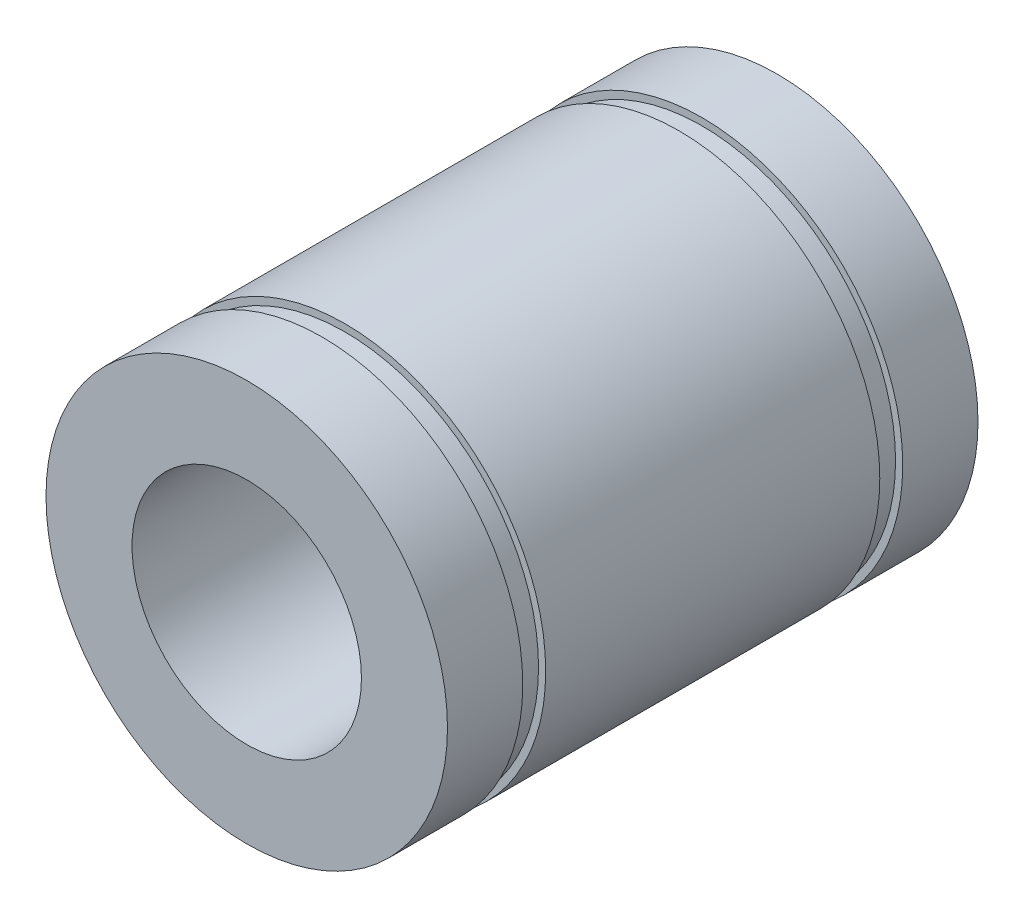
SolidWorks part; units mm, degrees
material "镀铬不锈钢"
ref_plane "前视基准面" through (0, 0, 0) normal (0, 0, 1) x (1, 0, 0)
ref_plane "上视基准面" through (0, 0, 0) normal (0, 1, 0) x (1, 0, 0)
ref_plane "右视基准面" through (0, 0, 0) normal (1, 0, 0) x (0, 0, -1)
sketch "草图1" plane through (0, 0, 0) normal (0, 0, 1) x (1, 0, 0)
  circle A0 centre (0, 0) radius 14
  circle A1 centre (0, 0) radius 8
  dimension "D1" = 28
  dimension "D2" = 16
extrude "凸台-拉伸1" add sketch "草图1" along normal mid plane 37
sketch "草图2" plane through (0, 0, 0) normal (0, 1, 0) x (1, 0, 0)
  line L0 (14, -18.5) -> (14, 18.5) construction
  line L1 (13.5, 13.25) -> (14, 13.25)
  line L2 (13.5, 13.25) -> (13.5, 11.65)
  line L3 (13.5, 11.65) -> (14, 11.65)
  line L4 (14, 13.25) -> (14, 11.65)
  line L5 (13.5, 13.25) -> (14, 11.65) construction
  line L6 (13.5, 11.65) -> (14, 13.25) construction
  line L7 (0, 0) -> (27.5415, 0) construction
  line L8 (13.5, -11.65) -> (14, -13.25) construction
  line L9 (13.5, -13.25) -> (14, -11.65) construction
  line L10 (14, -13.25) -> (14, -11.65)
  line L11 (13.5, -11.65) -> (14, -11.65)
  line L12 (13.5, -13.25) -> (13.5, -11.65)
  line L13 (13.5, -13.25) -> (14, -13.25)
  point P0 (13.75, 12.45)
  point P14 (13.75, -12.45)
  dimension "D1" = 26.5
  dimension "D2" = 1.6
  dimension "D3" = 13.5
revolve "切除-旋转1" cut sketch "草图2" angle 360 about axis through (0, 0, 18.5) along (0, 0, -1)
